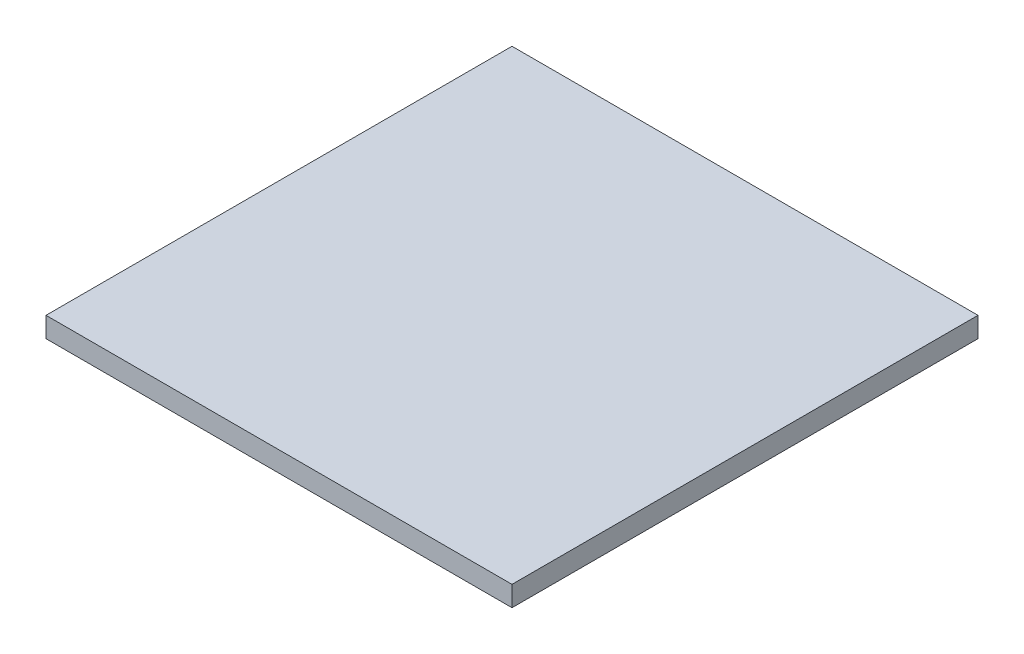
SolidWorks part; units mm, degrees
ref_plane "Front Plane" through (0, 0, 0) normal (0, 0, 1) x (1, 0, 0)
ref_plane "Top Plane" through (0, 0, 0) normal (0, 1, 0) x (1, 0, 0)
ref_plane "Right Plane" through (0, 0, 0) normal (1, 0, 0) x (0, 0, -1)
sketch "Sketch2" plane through (0, 0, 0) normal (0, 1, 0) x (1, 0, 0)
  line L1 (-146.05, -146.05) -> (146.05, -146.05)
  line L2 (-146.05, -146.05) -> (-146.05, 146.05)
  line L3 (-146.05, 146.05) -> (146.05, 146.05)
  line L4 (146.05, -146.05) -> (146.05, 146.05)
  line L5 (-146.05, -146.05) -> (146.05, 146.05) construction
  line L6 (-146.05, 146.05) -> (146.05, -146.05) construction
  point P0 (0, 0)
  dimension "D1" = 292.1
  dimension "D2" = 292.1
extrude "Boss-Extrude1" add sketch "Sketch2" along normal blind 12.7
